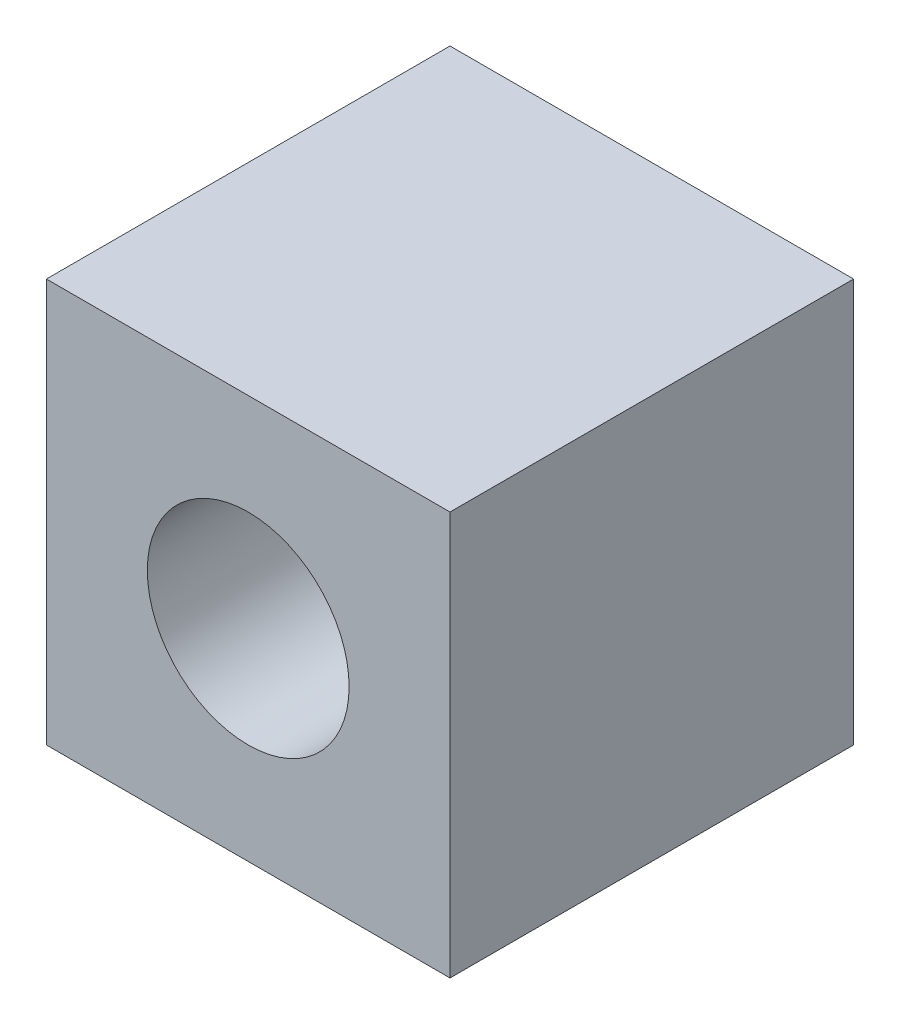
SolidWorks part; units mm, degrees
ref_plane "Front Plane" through (0, 0, 0) normal (0, 0, 1) x (1, 0, 0)
ref_plane "Top Plane" through (0, 0, 0) normal (0, 1, 0) x (1, 0, 0)
ref_plane "Right Plane" through (0, 0, 0) normal (1, 0, 0) x (0, 0, -1)
sketch "Sketch2" plane through (0, 0, 0) normal (0, 1, 0) x (1, 0, 0)
  line L1 (50, -50) -> (-50, -50)
  line L2 (50, -50) -> (50, 50)
  line L3 (50, 50) -> (-50, 50)
  line L4 (-50, -50) -> (-50, 50)
  line L5 (50, -50) -> (-50, 50) construction
  line L6 (50, 50) -> (-50, -50) construction
  point P0 (0, 0)
  dimension "D1" = 100
  dimension "D2" = 100
extrude "Boss-Extrude1" add sketch "Sketch2" along normal blind 100
sketch "Sketch3" plane through (0, 0, 50) normal (0, 0, 1) x (1, 0, 0)
  line L0 (0, 0) -> (0, 100) construction
  line L1 (-50, 100) -> (50, 100) construction
  circle A0 centre (0, 50) radius 25
  dimension "D1" = 50
extrude "Cut-Extrude1" cut sketch "Sketch3" against normal through all
